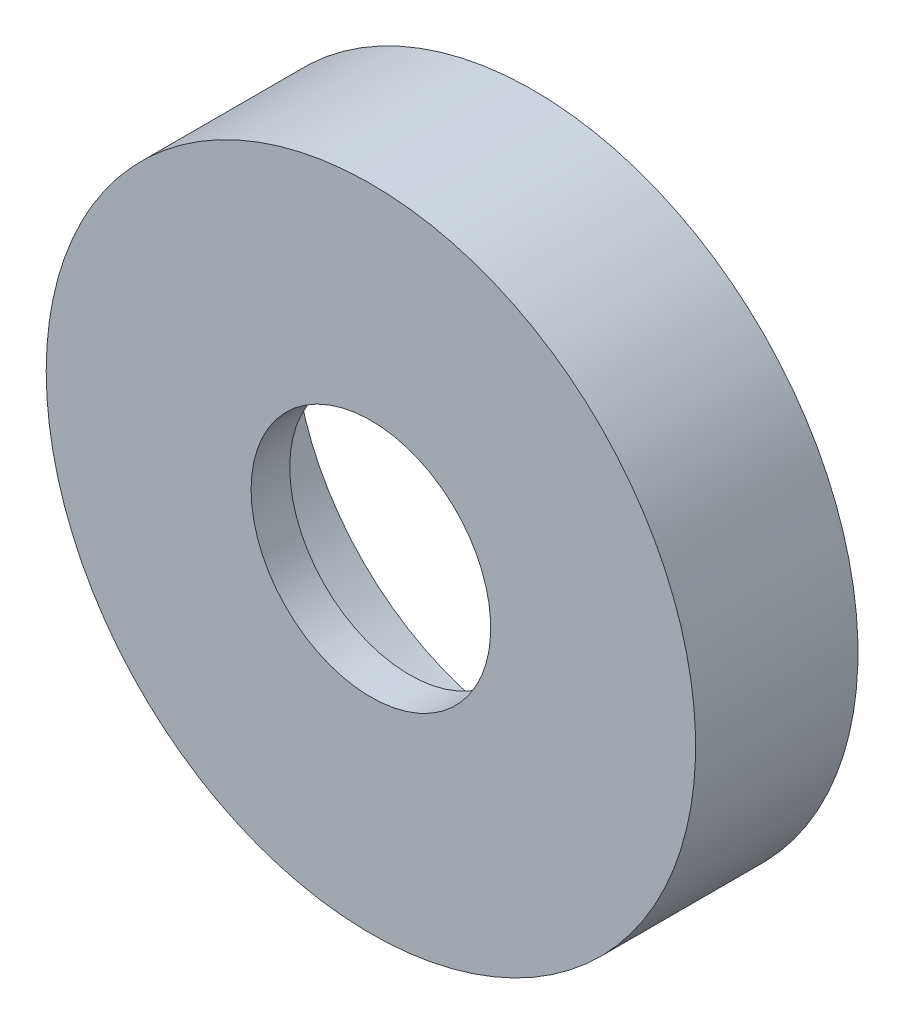
SolidWorks part; units mm, degrees
ref_plane "Спереди" through (0, 0, 0) normal (0, 0, 1) x (1, 0, 0)
ref_plane "Сверху" through (0, 0, 0) normal (0, 1, 0) x (1, 0, 0)
ref_plane "Справа" through (0, 0, 0) normal (1, 0, 0) x (0, 0, -1)
sketch "Эскиз1" plane through (0, 0, 0) normal (0, 0, 1) x (1, 0, 0)
  circle A0 centre (0, 0) radius 42
extrude "Вытянуть1" add sketch "Эскиз1" along normal blind 21
sketch "Эскиз2" plane through (0, 0, 0) normal (0, 0, -1) x (-1, 0, 0)
  circle A0 centre (0, 0) radius 31
extrude "Вытянуть2" cut sketch "Эскиз2" against normal blind 16
sketch "Эскиз3" plane through (0, 0, 16) normal (0, 0, -1) x (-1, 0, 0)
  circle A0 centre (0, 0) radius 15.5
extrude "Вытянуть3" cut sketch "Эскиз3" against normal through all
